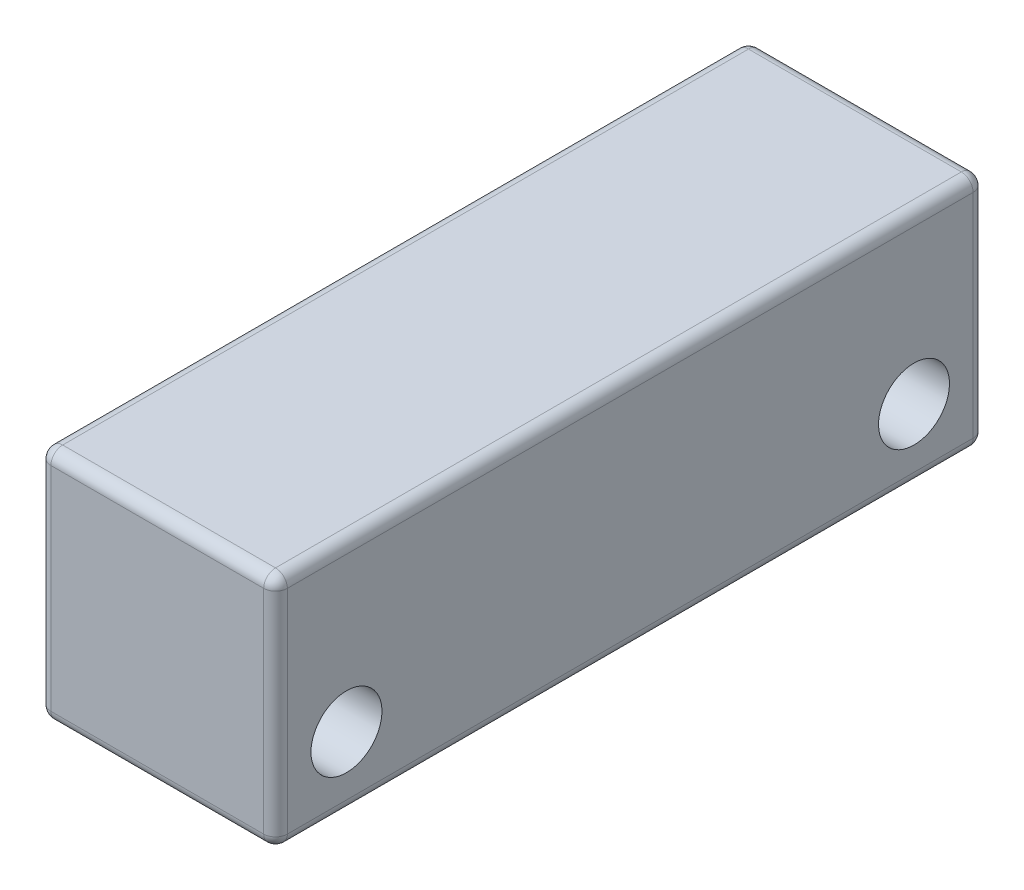
SolidWorks part; units mm, degrees
ref_plane "Plan de face" through (0, 0, 0) normal (0, 0, 1) x (1, 0, 0)
ref_plane "Plan de dessus" through (0, 0, 0) normal (0, 1, 0) x (1, 0, 0)
ref_plane "Plan de droite" through (0, 0, 0) normal (1, 0, 0) x (0, 0, -1)
sketch "Esquisse1" plane through (0, 0, 0) normal (0, 0, 1) x (1, 0, 0)
  line L1 (-5, 5) -> (5, 5)
  line L2 (-5, 5) -> (-5, -5)
  line L3 (-5, -5) -> (5, -5)
  line L4 (5, 5) -> (5, -5)
  line L5 (-5, 5) -> (5, -5) construction
  line L6 (-5, -5) -> (5, 5) construction
  point P0 (0, 0)
  dimension "10" = 10
  dimension "D2" = 10
extrude "Boss.-Extru.1" add sketch "Esquisse1" along normal blind 30
sketch "Esquisse2" plane through (5, 0, 0) normal (1, 0, 0) x (0, 0, -1)
  line L0 (-30, -5) -> (0, -5) construction
  line L1 (0, -5) -> (0, 5) construction
  circle A0 centre (-3, -2) radius 1.5
  dimension "D3" = 3
  dimension "D1" = 3
  dimension "D2" = 3
extrude "Enlèv. mat.-Extru.1" cut sketch "Esquisse2" against normal blind 30
fillet "Congé1" radius 0.5 12 edges at (5, 0, 30) (5, 0, 0) (5, 5, 15) (0, 5, 30) (0, 5, 0) (-5, 5, 15) (-5, 0, 30) (-5, 0, 0) (-5, -5, 15) (0, -5, 30) (5, -5, 15) (0, -5, 0)
sketch "Esquisse3" plane through (-5, 0, 0) normal (-1, 0, 0) x (0, 0, 1)
  line L0 (3, -2) -> (27, -2) construction
  circle A0 centre (27, -2) radius 1.5
  dimension "D2" = 3
  dimension "D1" = 24
extrude "Enlèv. mat.-Extru.2" cut sketch "Esquisse3" against normal blind 10
